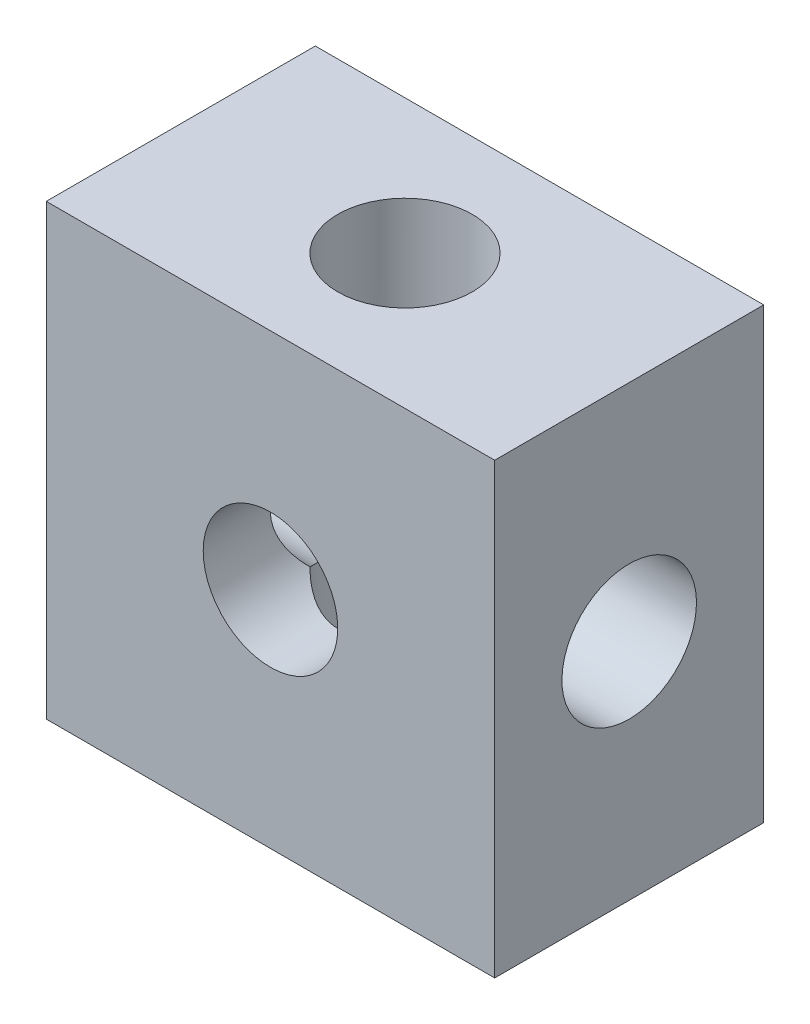
SolidWorks part; units mm, degrees
material "铸造不锈钢"
ref_plane "前视基准面" through (0, 0, 0) normal (0, 0, 1) x (1, 0, 0)
ref_plane "上视基准面" through (0, 0, 0) normal (0, 1, 0) x (1, 0, 0)
ref_plane "右视基准面" through (0, 0, 0) normal (1, 0, 0) x (0, 0, -1)
sketch "草图1" plane through (0, 0, 0) normal (0, 0, 1) x (1, 0, 0)
  line L1 (-5, 5) -> (5, 5)
  line L2 (-5, 5) -> (-5, -5)
  line L3 (-5, -5) -> (5, -5)
  line L4 (5, 5) -> (5, -5)
  line L5 (-5, 5) -> (5, -5) construction
  line L6 (-5, -5) -> (5, 5) construction
  point P0 (0, 0)
  dimension "D1" = 10
  dimension "D2" = 10
extrude "凸台-拉伸1" add sketch "草图1" along normal mid plane 6
sketch "草图2" plane through (0, 5, 0) normal (0, 1, 0) x (1, 0, 0)
  circle A0 centre (0, 0) radius 1.5
  dimension "D1" = 3
extrude "切除-拉伸1" cut sketch "草图2" against normal through all
sketch "草图3" plane through (-5, 0, 0) normal (-1, 0, 0) x (0, 0, 1)
  circle A0 centre (0, 0) radius 1.5
  dimension "D1" = 3
extrude "切除-拉伸2" cut sketch "草图3" against normal through all
sketch "草图4" plane through (0, 0, -3) normal (0, 0, -1) x (-1, 0, 0)
  circle A0 centre (0, 0) radius 1.5
  dimension "D1" = 3
extrude "切除-拉伸3" cut sketch "草图4" against normal through all
